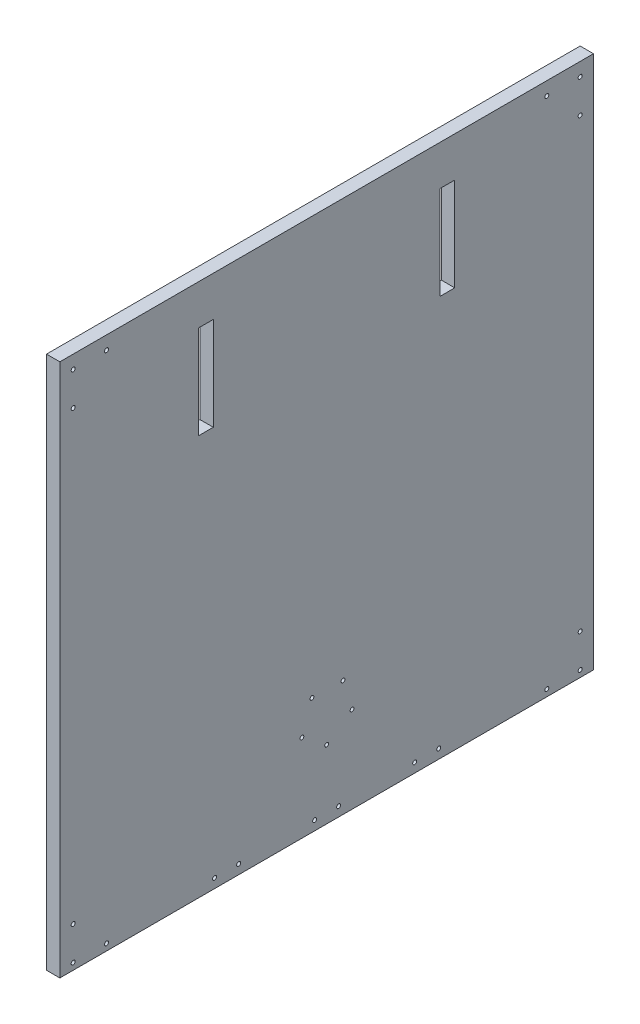
SolidWorks part; units mm, degrees
ref_plane "前视基准面" through (0, 0, 0) normal (0, 0, 1) x (1, 0, 0)
ref_plane "上视基准面" through (0, 0, 0) normal (0, 1, 0) x (1, 0, 0)
ref_plane "右视基准面" through (0, 0, 0) normal (1, 0, 0) x (0, 0, -1)
sketch "草图1" plane through (0, 0, 0) normal (1, 0, 0) x (0, 0, -1)
  line L1 (-200, 200) -> (200, 200)
  line L2 (-200, 200) -> (-200, -200)
  line L3 (-200, -200) -> (200, -200)
  line L4 (200, 200) -> (200, -200)
  line L5 (-200, 200) -> (200, -200) construction
  line L6 (-200, -200) -> (200, 200) construction
  point P0 (0, 0)
  dimension "D1" = 400
  dimension "D2" = 400
extrude "凸台-拉伸1" add sketch "草图1" along normal blind 10
sketch "草图2" plane through (10, 0, 0) normal (1, 0, 0) x (0, 0, -1)
  line L0 (200, 200) -> (200, -200) construction
  line L3 (165, 190) -> (190, 190) construction
  line L4 (190, 165) -> (190, 190) construction
  line L5 (165, -195) -> (190, -195) construction
  line L6 (165, 190) -> (190, 165) construction
  line L7 (-200, 200) -> (200, 200) construction
  line L8 (190, -195) -> (190, -170) construction
  line L9 (-200, -200) -> (200, -200) construction
  circle A0 centre (190, 190) radius 1.5
  circle A1 centre (165, 190) radius 1.5
  circle A2 centre (190, 165) radius 1.5
  circle A3 centre (190, -195) radius 1.5
  circle A4 centre (165, -195) radius 1.5
  circle A5 centre (190, -170) radius 1.5
  point P0 (176.0995, 178.9005)
  dimension "D5" = 3
  dimension "D6" = 3
  dimension "D7" = 3
  dimension "D1" = 25
  dimension "D2" = 25
  dimension "D3" = 10
  dimension "D4" = 10
  dimension "D8" = 25
  dimension "D9" = 25
  dimension "D10" = 5
  dimension "D11" = 10
extrude "切除-拉伸1" cut sketch "草图2" against normal blind 10
sketch "草图3" plane through (10, 0, 0) normal (1, 0, 0) x (0, 0, -1)
  line L0 (-84, -193) -> (-66, -193) construction
  line L1 (-66, -193) -> (-9, -193) construction
  line L2 (-9, -193) -> (9, -193) construction
  line L3 (9, -193) -> (66, -193) construction
  line L4 (66, -193) -> (84, -193) construction
  line L5 (-200, -200) -> (200, -200) construction
  line L6 (-200, 200) -> (-200, -200) construction
  circle A0 centre (-84, -193) radius 1.5
  circle A1 centre (-66, -193) radius 1.5
  circle A2 centre (-9, -193) radius 1.5
  circle A3 centre (9, -193) radius 1.5
  circle A4 centre (66, -193) radius 1.5
  circle A5 centre (84, -193) radius 1.5
  dimension "D1" = 3
  dimension "D2" = 3
  dimension "D3" = 3
  dimension "D4" = 3
  dimension "D5" = 3
  dimension "D6" = 3
  dimension "D7" = 7
  dimension "D8" = 116
  dimension "D9" = 18
  dimension "D10" = 18
  dimension "D11" = 18
  dimension "D12" = 57
  dimension "D13" = 57
extrude "切除-拉伸2" cut sketch "草图3" against normal blind 10
mirror "镜向1" about plane through (0, 0, 0) normal (0, 0, 1) of "切除-拉伸1"
sketch "草图4" plane through (10, 0, 0) normal (1, 0, 0) x (0, 0, -1)
  line L0 (-200, -200) -> (200, -200) construction
  line L1 (19.0413, -135.2539) -> (12.238, -113.0222) construction
  line L2 (12.238, -113.0222) -> (-11.0079, -112.6225) construction
  line L3 (-11.0079, -112.6225) -> (-18.5714, -134.6072) construction
  line L4 (-18.5714, -134.6072) -> (0, -148.5942) construction
  line L5 (0, -148.5942) -> (19.0413, -135.2539) construction
  line L7 (200, 200) -> (200, -200) construction
  circle A0 centre (0.34, -128.82) radius 16 construction
  circle A1 centre (-11.0079, -112.6225) radius 1.45
  circle A2 centre (12.238, -113.0222) radius 1.45
  circle A3 centre (-18.5714, -134.6072) radius 1.45
  circle A4 centre (19.0413, -135.2539) radius 1.45
  circle A5 centre (0, -148.5942) radius 1.45
  dimension "D1" = 32
  dimension "D3" = 2.9
  dimension "D4" = 2.9
  dimension "D5" = 2.9
  dimension "D6" = 2.9
  dimension "D7" = 2.9
  dimension "D2" = 71.18
  dimension "D8" = 199.66
extrude "切除-拉伸3" cut sketch "草图4" against normal blind 10
sketch "草图5" plane through (0, 0, 0) normal (1, 0, 0) x (0, 0, -1)
  line L0 (-85, 200) -> (85, 200)
  line L1 (-200, 200) -> (200, 200) construction
  line L2 (0, 0) -> (0, 200) construction
  line L3 (-85, 200) -> (-85, 170)
  line L4 (-85, 170) -> (-85, 100)
  line L5 (-96, 100) -> (-96, 170)
  line L6 (-85, 100) -> (-96, 100)
  line L7 (-96, 170) -> (-85, 170)
  line L8 (85, 100) -> (96, 100)
  line L9 (96, 170) -> (85, 170)
  line L10 (85, 170) -> (85, 100)
  line L11 (96, 100) -> (96, 170)
  point P5 (0, 200)
extrude "切除-拉伸5" cut sketch "草图5" along normal blind 10 contours L4 L6 L5 L7 | L11 L9 L10 L8
